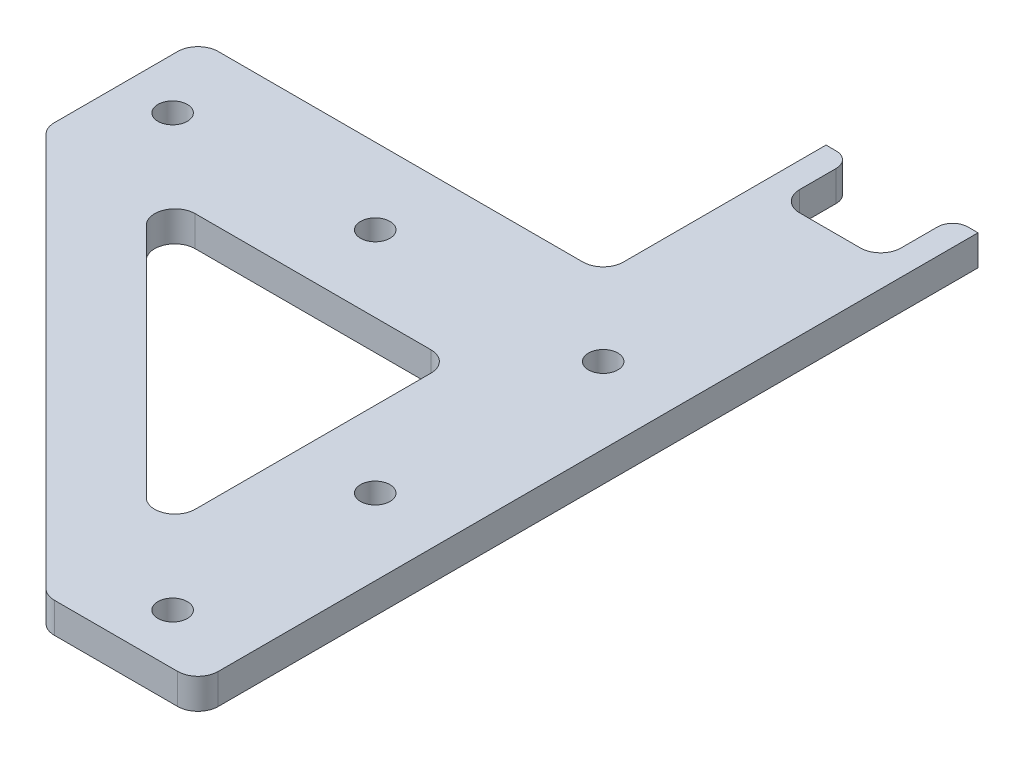
SolidWorks part; units mm, degrees
material "Thornel Mat VMA"
ref_plane "前视基准面" through (0, 0, 0) normal (0, 0, 1) x (1, 0, 0)
ref_plane "上视基准面" through (0, 0, 0) normal (0, 1, 0) x (1, 0, 0)
ref_plane "右视基准面" through (0, 0, 0) normal (1, 0, 0) x (0, 0, -1)
other "Configuration Table"
sketch "草图1" plane through (0, 0, 0) normal (0, 1, 0) x (1, 0, 0)
  line L0 (-47.5, 0) -> (0, 0)
  line L1 (7.5, -15) -> (7.5, -55)
  line L2 (7.5, -55) -> (-7.5, -55)
  line L3 (-7.5, -55) -> (-7.5, -15)
  line L4 (-7.5, -15) -> (-47.5, -15)
  line L5 (-47.5, -15) -> (-47.5, 0)
  line L6 (-47.5, -7.5) -> (47.5, -7.5) construction
  line L7 (0, -55) -> (0, 0) construction
  line L8 (7.5, -15) -> (47.5, -15)
  line L9 (47.5, -15) -> (47.5, 0)
  line L10 (0, 0) -> (47.5, 0)
  circle A0 centre (0, -7.5) radius 1.45
  circle A1 centre (0, -30) radius 1.45
  circle A2 centre (0, -50) radius 1.45
  circle A3 centre (-22.5, -7.5) radius 1.45
  circle A4 centre (-42.5, -7.5) radius 1.45
  circle A5 centre (42.5, -7.5) radius 1.45
  circle A6 centre (22.5, -7.5) radius 1.45
  dimension "D3" = 2.9
  dimension "D4" = 2.9
  dimension "D5" = 2.9
  dimension "D9" = 2.9
  dimension "D10" = 2.9
  dimension "D11" = 22.5
  dimension "D12" = 20
  dimension "D13" = 5
  dimension "D1" = 15
  dimension "D2" = 15
  dimension "D6" = 22.5
  dimension "D7" = 20
  dimension "D8" = 5
extrude "凸台-拉伸1" add sketch "草图1" along normal blind 3
sketch "草图2" plane through (0, 3, 0) normal (0, 1, 0) x (1, 0, 0)
  line L0 (-47.5, -15) -> (-7.5, -55)
  line L1 (-7.5, -55) -> (-7.5, -45.1005)
  line L2 (-7.5, -15) -> (-7.5, -55) construction
  line L3 (-7.5, -45.1005) -> (-37.6005, -15)
  line L4 (-47.5, -15) -> (-7.5, -15) construction
  line L5 (-37.6005, -15) -> (-47.5, -15)
  line L6 (0, 0) -> (0, -55) construction
  line L7 (-7.5, -55) -> (7.5, -55) construction
  line L8 (37.6005, -15) -> (47.5, -15)
  line L9 (7.5, -45.1005) -> (37.6005, -15)
  line L10 (7.5, -55) -> (7.5, -45.1005)
  line L11 (47.5, -15) -> (7.5, -55)
  dimension "D1" = 7
extrude "凸台-拉伸2" add sketch "草图2" against normal up to surface (3 mm away) up to face at (42.5, 0, 6.05)
sketch "草图4" plane through (0, 3, 0) normal (0, 1, 0) x (1, 0, 0)
  line L0 (7.5, -55) -> (7.5, 0)
  line L1 (47.5, 0) -> (-47.5, 0) construction
  line L2 (7.5, 0) -> (47.5, 0)
  line L3 (47.5, 0) -> (47.5, -55)
  line L4 (47.5, -55) -> (7.5, -55)
  line L5 (47.5, -15) -> (47.5, 0) construction
extrude "切除-拉伸2" cut sketch "草图4" against normal through all
sketch "草图5" plane through (0, 3, 0) normal (0, 1, 0) x (1, 0, 0)
  line L0 (7.5, 0) -> (-47.5, 0) construction
  line L1 (-7.5, 0) -> (7.5, 0)
  line L2 (-7.5, 0) -> (-7.5, 22)
  line L3 (-7.5, 22) -> (7.5, 22)
  line L4 (7.5, 0) -> (7.5, 22)
  line L5 (-7.5, -15) -> (-7.5, -45.1005) construction
  line L6 (7.5, -55) -> (7.5, 0) construction
  dimension "D1" = 22
extrude "凸台-拉伸3" add sketch "草图5" against normal up to surface (3 mm away) up to face at (-17.5, 0, 25)
sketch "草图6" plane through (0, 3, 0) normal (0, 1, 0) x (1, 0, 0)
  line L0 (7.5, 22) -> (-7.5, 22) construction
  line L1 (-5, 22) -> (5, 22)
  line L2 (-5, 22) -> (-5, 14.9)
  line L3 (-5, 14.9) -> (5, 14.9)
  line L4 (5, 22) -> (5, 14.9)
  line L5 (-7.5, 0) -> (-47.5, 0) construction
  line L6 (0, 22) -> (0, 0) construction
  dimension "D1" = 14.9
  dimension "D2" = 10
extrude "切除-拉伸3" cut sketch "草图6" against normal through all
fillet "圆角1" radius 2 10 edges at (-7.5, 1.5, 45.1005) (-37.6005, 1.5, 15) (-7.5, 1.5, 15) (5, 1.5, -14.9) (7.5, 1.5, 55) (-7.5, 1.5, 55) (-5, 1.5, -14.9) (-47.5, 1.5, 15) (-47.5, 1.5, 0) (-7.5, 1.5, 0)
fillet "圆角2" radius 1.5 2 edges at (5, 1.5, -22) (-5, 1.5, -22)
